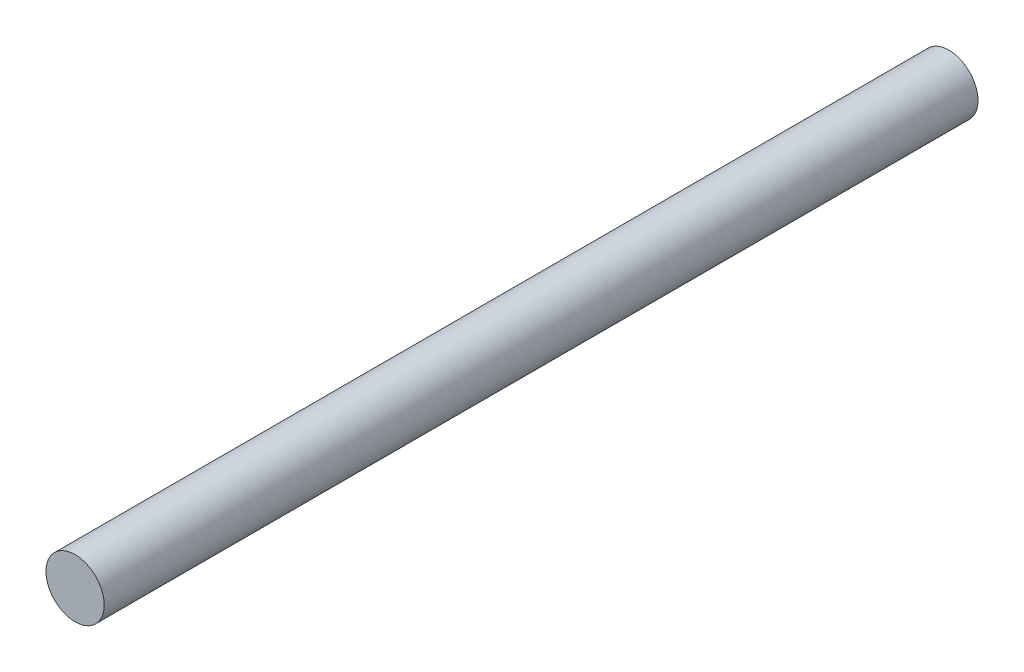
SolidWorks part; units mm, degrees
ref_plane "正面" through (0, 0, 0) normal (0, 0, 1) x (1, 0, 0)
ref_plane "平面" through (0, 0, 0) normal (0, 1, 0) x (1, 0, 0)
ref_plane "右側面" through (0, 0, 0) normal (1, 0, 0) x (0, 0, -1)
sketch "ｽｹｯﾁ1" plane through (0, 0, 0) normal (0, 0, 1) x (1, 0, 0)
  circle A0 centre (0, 0) radius 2.5
  dimension "D1" = 5
extrude "ﾎﾞｽ - 押し出し2" add sketch "ｽｹｯﾁ1" along normal blind 75
